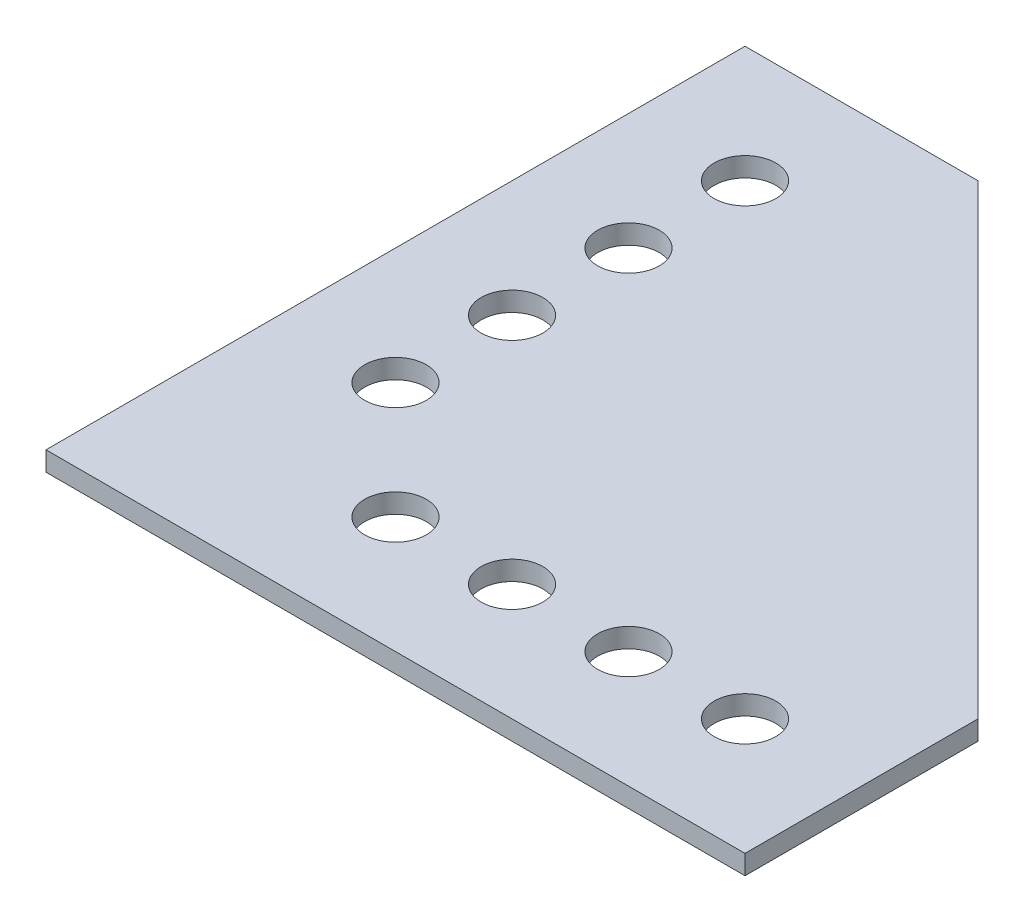
SolidWorks part; units mm, degrees
ref_plane "Front Plane" through (0, 0, 0) normal (0, 0, 1) x (1, 0, 0)
ref_plane "Top Plane" through (0, 0, 0) normal (0, 1, 0) x (1, 0, 0)
ref_plane "Right Plane" through (0, 0, 0) normal (1, 0, 0) x (0, 0, -1)
sketch "Sketch1" plane through (0, 0, 0) normal (0, 1, 0) x (1, 0, 0)
  line L0 (0, 0) -> (38.1, 0)
  line L1 (0, 0) -> (0, -114.3)
  line L2 (0, -114.3) -> (114.3, -114.3)
  line L3 (114.3, -114.3) -> (114.3, -76.2)
  line L4 (114.3, -76.2) -> (38.1, 0)
  line L5 (19.05, 0) -> (19.05, -19.05) construction
  line L6 (19.05, -19.05) -> (19.05, -38.1) construction
  line L7 (19.05, -38.1) -> (19.05, -57.15) construction
  line L8 (19.05, -57.15) -> (19.05, -76.2) construction
  line L9 (114.3, -95.25) -> (95.25, -95.25) construction
  line L10 (95.25, -95.25) -> (76.2, -95.25) construction
  line L11 (76.2, -95.25) -> (57.15, -95.25) construction
  line L12 (57.15, -95.25) -> (38.1, -95.25) construction
  dimension "D1" = 38.1
  dimension "D2" = 114.3
  dimension "D3" = 114.3
  dimension "D4" = 38.1
  dimension "D5" = 19.05
  dimension "D6" = 19.05
  dimension "D7" = 19.05
  dimension "D8" = 19.05
  dimension "D9" = 19.05
  dimension "D10" = 19.05
  dimension "D11" = 19.05
  dimension "D12" = 19.05
extrude "Boss-Extrude1" add sketch "Sketch1" along normal blind 3.175
hole_wizard "3/8 Clearance Hole1" positions "Sketch2" profile "Sketch3" hole size "3/8" standard "ANSI Inch"
sketch "Sketch2" plane through (0, 3.175, 0) normal (0, 1, 0) x (1, 0, 0)
  point P0 (19.05, -19.05)
  point P3 (19.05, -38.1)
  point P6 (19.05, -57.15)
  point P9 (19.05, -76.2)
  point P12 (38.1, -95.25)
  point P15 (57.15, -95.25)
  point P18 (76.2, -95.25)
  point P21 (95.25, -95.25)
sketch "Sketch3" plane through (19.05, 3.175, 19.05) normal (1, 0, 0) x (0, 0, 1)
  line L0 (0, 0) -> (0, 6.2045)
  line L1 (0, 6.2045) -> (5.0419, 3.175)
  line L2 (5.0419, 3.175) -> (5.0419, 0)
  line L5 (5.0419, 0) -> (0, 0)
  line L10 (0, 6.2045) -> (-5.0419, 3.175) construction
  line L11 (0, -6.35) -> (0, 107.95) construction
  dimension "Hole Dia." = 10.0838
  dimension "Hole Depth" = 3.175
  dimension "Drill Angle" = 118
